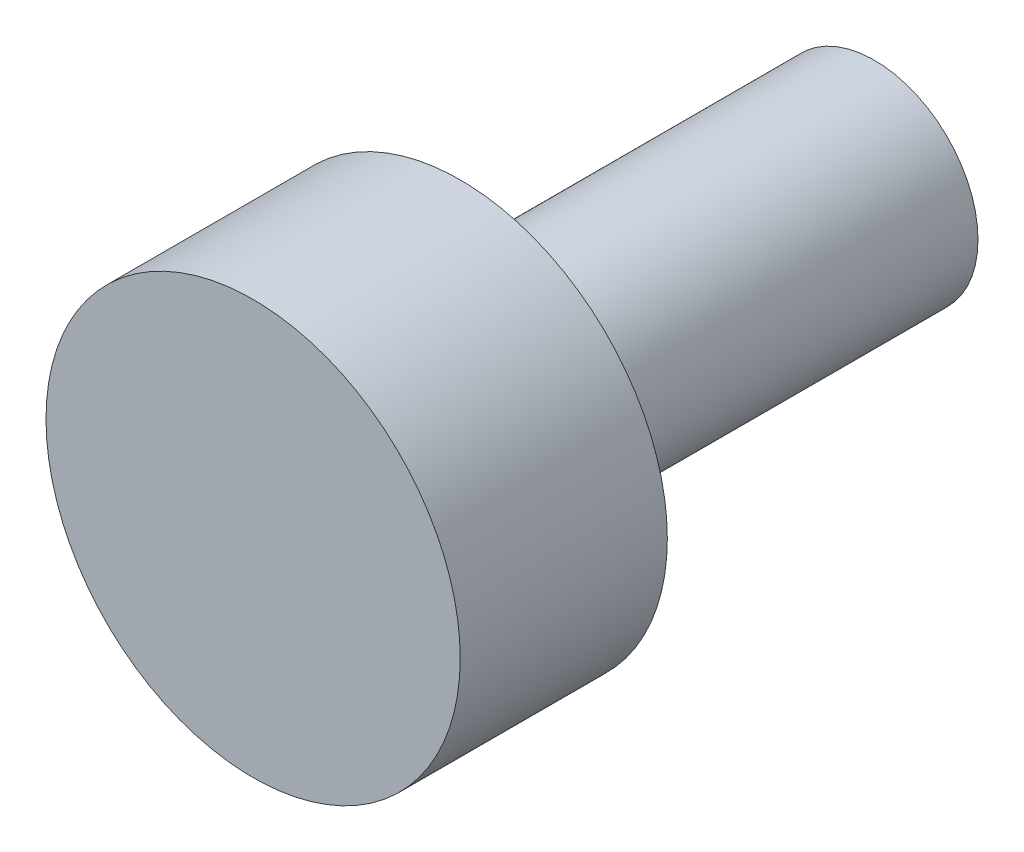
SolidWorks part; units mm, degrees
ref_plane "Front Plane" through (0, 0, 0) normal (0, 0, 1) x (1, 0, 0)
ref_plane "Top Plane" through (0, 0, 0) normal (0, 1, 0) x (1, 0, 0)
ref_plane "Right Plane" through (0, 0, 0) normal (1, 0, 0) x (0, 0, -1)
sketch "Sketch1" plane through (0, 0, 0) normal (0, 0, 1) x (1, 0, 0)
  circle A0 centre (0, 0) radius 25.4
  dimension "D1" = 50.8
extrude "Boss-Extrude2" add sketch "Sketch1" along normal blind 25.4
sketch "Sketch2" plane through (0, 0, 0) normal (0, 0, 1) x (1, 0, 0)
  circle A0 centre (0, 0) radius 12.7
extrude "Boss-Extrude4" add sketch "Sketch2" against normal blind 50.8
